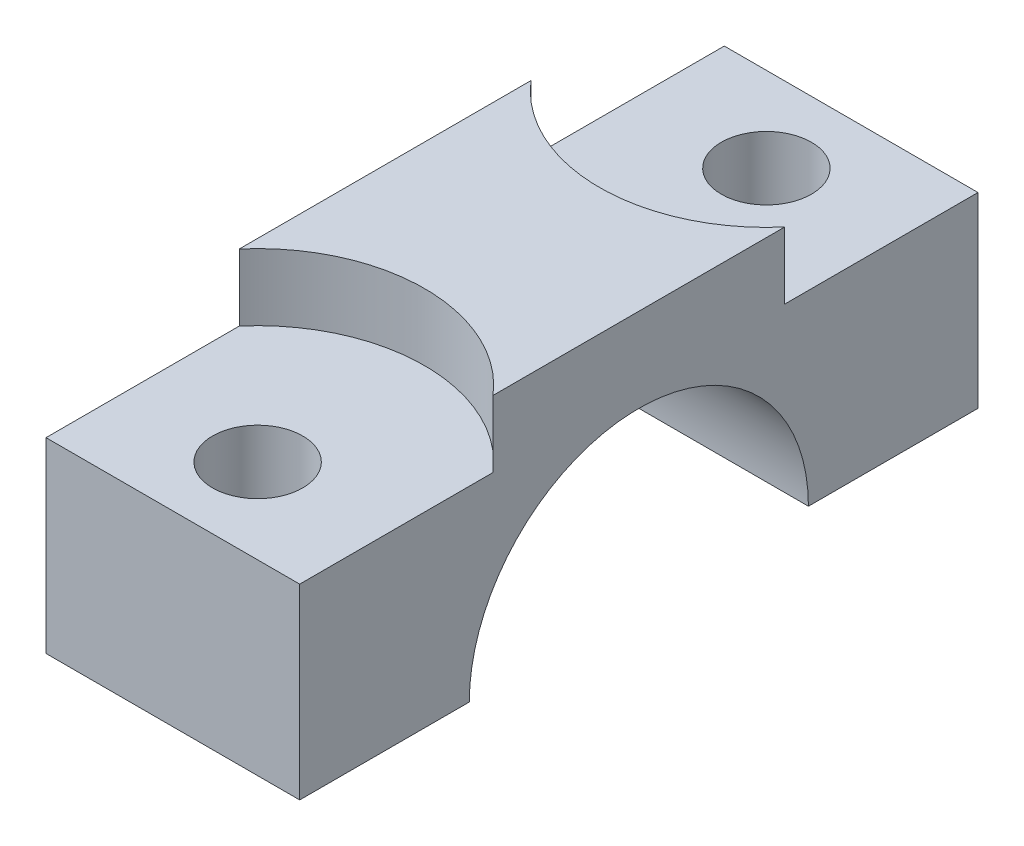
SolidWorks part; units mm, degrees
material "Gray Cast Iron (SN)"
ref_plane "Front Plane" through (0, 0, 0) normal (0, 0, 1) x (1, 0, 0)
ref_plane "Top Plane" through (0, 0, 0) normal (0, 1, 0) x (1, 0, 0)
ref_plane "Right Plane" through (0, 0, 0) normal (1, 0, 0) x (0, 0, -1)
sketch "Sketch1" plane through (0, 0, 0) normal (1, 0, 0) x (0, 0, -1)
  line L1 (-25.4, 19) -> (25.4, 19)
  line L2 (-25.4, 19) -> (-25.4, 0)
  line L3 (-25.4, 0) -> (25.4, 0)
  line L4 (25.4, 19) -> (25.4, 0)
  circle A0 centre (0, 0) radius 12.7
  dimension "D3" = 25.4
  dimension "D1" = 50.8
  dimension "D2" = 19
extrude "Boss-Extrude1" add sketch "Sketch1" along normal mid plane 19 contours A0 L3 L4 L1 L2
sketch "Sketch2" plane through (0, 0, 0) normal (0, -1, 0) x (1, 0, 0)
  line L0 (0, 25.4) -> (0, 12.7) construction
  line L1 (9.5, 25.4) -> (-9.5, 25.4) construction
  line L2 (9.5, 12.7) -> (-9.5, 12.7) construction
  line L3 (0, -12.7) -> (0, -25.4) construction
  line L4 (9.5, -12.7) -> (-9.5, -12.7) construction
  line L5 (9.5, -25.4) -> (-9.5, -25.4) construction
  point P12 (0, 19.05)
  point P13 (0, -19.05)
hole_wizard "CBORE for M12 Hex Head Cap Screw1" positions "Sketch3" profile "Sketch4" counterbore size "M12" standard "ISO" end condition through all
sketch "Sketch3" plane through (0, 19, 0) normal (0, 1, 0) x (1, 0, 0)
  point P0 (0, -19.05)
  point P3 (0, 19.05)
sketch "Sketch4" plane through (0, 19, 19.05) normal (1, 0, 0) x (0, 0, 1)
  line L0 (0, 0) -> (0, 19)
  line L1 (0, 19) -> (3.375, 19)
  line L3 (3.375, 19) -> (3.375, 5)
  line L4 (3.375, 5) -> (12.5, 5)
  line L5 (12.5, 5) -> (12.5, 0)
  line L7 (12.5, 0) -> (0, 0)
  line L11 (0, -6.35) -> (0, 107.95) construction
  dimension "Thru Hole Dia." = 6.75
  dimension "Thru Hole Depth" = 19
  dimension "C'Bore Dia." = 25
  dimension "C'Bore Depth" = 5
